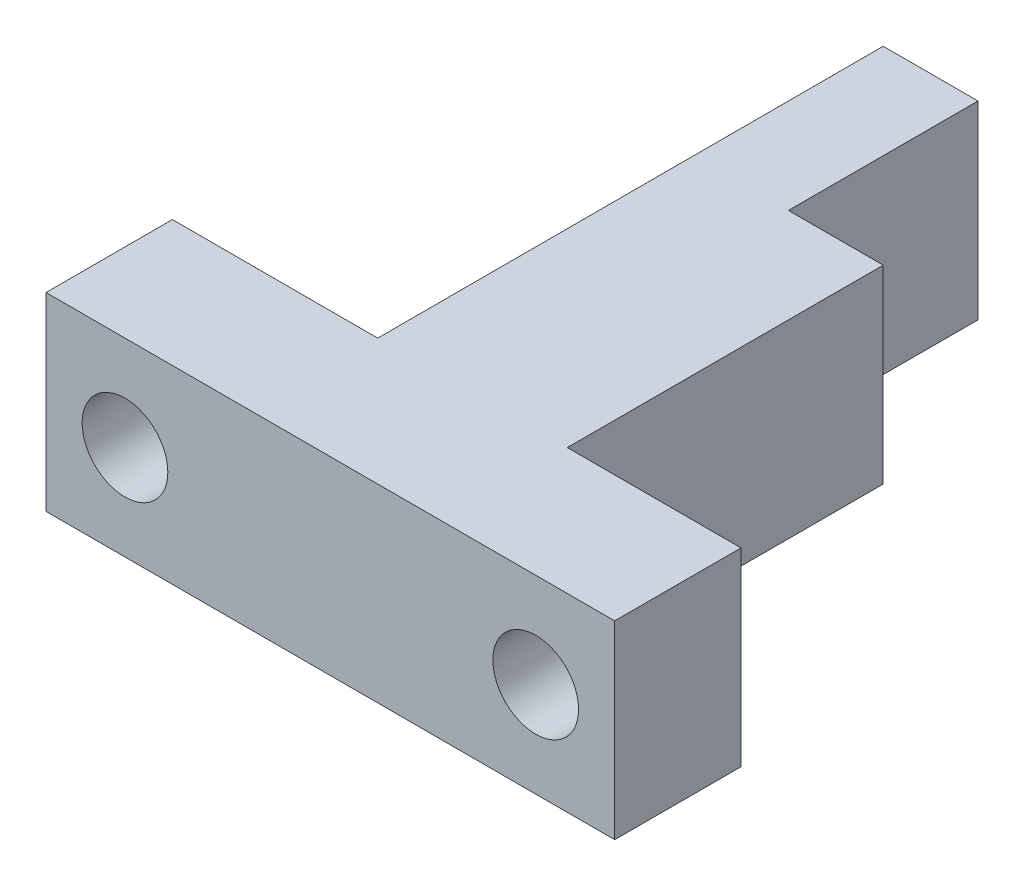
SolidWorks part; units mm, degrees
material "6061-T6 (SS)"
ref_plane "Front Plane" through (0, 0, 0) normal (0, 0, 1) x (1, 0, 0)
ref_plane "Top Plane" through (0, 0, 0) normal (0, 1, 0) x (1, 0, 0)
ref_plane "Right Plane" through (0, 0, 0) normal (1, 0, 0) x (0, 0, -1)
sketch "Sketch2" plane through (0, 0, 0) normal (0, 1, 0) x (1, 0, 0)
  line L0 (-14.2875, 0) -> (14.2875, 0)
  line L1 (-14.2875, 0) -> (-14.2875, 6.35)
  line L2 (-14.2875, 6.35) -> (-3.9688, 6.35)
  line L3 (-3.9688, 6.35) -> (-3.9688, 31.75)
  line L4 (-3.9688, 31.75) -> (0.7937, 31.75)
  line L5 (0.7937, 31.75) -> (0.7937, 22.225)
  line L6 (0.7937, 22.225) -> (5.5562, 22.225)
  line L7 (5.5562, 22.225) -> (5.5562, 6.35)
  line L8 (5.5562, 6.35) -> (14.2875, 6.35)
  line L9 (14.2875, 6.35) -> (14.2875, 0)
  line L10 (-10.3187, 6.35) -> (-10.3187, 0) construction
  line L11 (10.3187, 0) -> (10.3187, 6.35) construction
  point P2 (0, 0)
  dimension "D2" = 6.35
  dimension "D1" = 28.575
  dimension "D3" = 20.6375
  dimension "D4" = 10.3187
  dimension "D5" = 31.75
  dimension "D6" = 9.525
  dimension "D7" = 9.525
  dimension "D8" = 0.7937
extrude "Boss-Extrude1" add sketch "Sketch2" along normal blind 9.525
sketch "Sketch3" plane through (0, 0, 0) normal (0, 0, 1) x (1, 0, 0)
  circle A0 centre (-10.3188, 4.7625) radius 2.1527
  circle A1 centre (10.3187, 4.7625) radius 2.1526
  dimension "D1" = 4.3053
  dimension "D2" = 10.3187
  dimension "D4" = 4.7625
  dimension "D3" = 10.3187
  dimension "D5" = 4.7625
extrude "Cut-Extrude1" cut sketch "Sketch3" against normal through all
